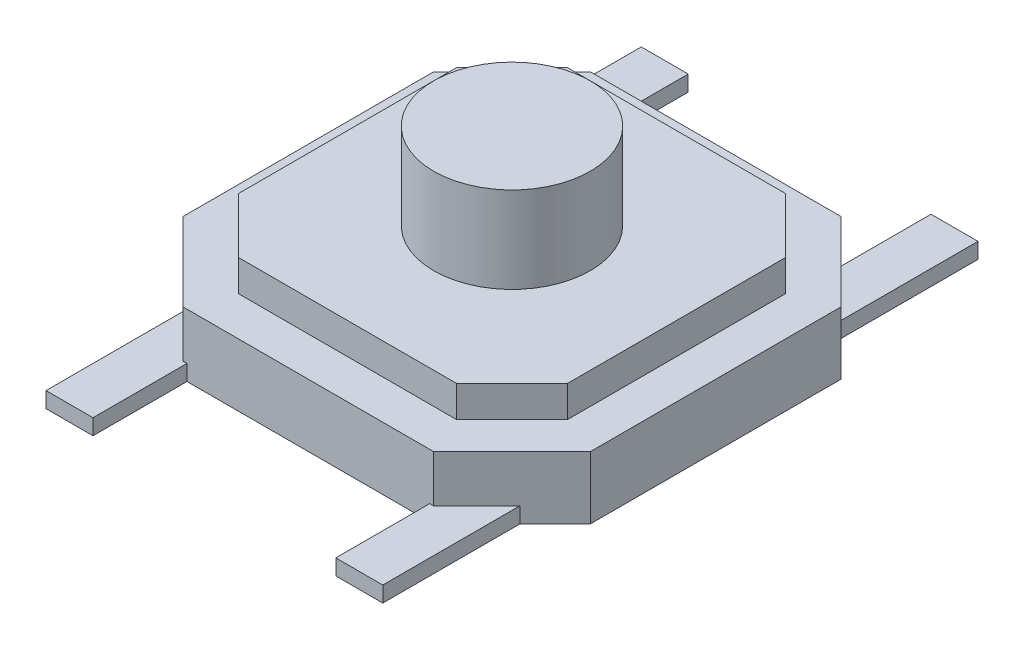
SolidWorks part; units mm, degrees
ref_plane "前视" through (0, 0, 0) normal (0, 0, 1) x (1, 0, 0)
ref_plane "上视" through (0, 0, 0) normal (0, 1, 0) x (1, 0, 0)
ref_plane "右视" through (0, 0, 0) normal (1, 0, 0) x (0, 0, -1)
sketch "草图1" plane through (0, 0, 0) normal (0, 1, 0) x (1, 0, 0)
  line L0 (0, 96.9306) -> (0, -101.3275) construction
  line L1 (-119.7143, 0) -> (134.9034, 0) construction
  line L3 (-2.6, 2.6) -> (2.6, 2.6)
  line L4 (-2.6, 2.6) -> (-2.6, -2.6)
  line L5 (-2.6, -2.6) -> (2.6, -2.6)
  line L6 (2.6, 2.6) -> (2.6, -2.6)
  dimension "D1" = 5.2
  dimension "D2" = 5.2
extrude "拉伸1" add sketch "草图1" along normal blind 0.8
chamfer "倒角1" distance 1 angle 45 4 edges at (2.6, 0.4, -2.6) (2.6, 0.4, 2.6) (-2.6, 0.4, 2.6) (-2.6, 0.4, -2.6)
sketch "草图3" plane through (0, 0.8, 0) normal (0, 1, 0) x (1, 0, 0)
  line L16 (-2.1, 1.3929) -> (-2.1, -1.3929)
  line L17 (-2.1, -1.3929) -> (-1.3929, -2.1)
  line L18 (-1.3929, -2.1) -> (1.3929, -2.1)
  line L19 (1.3929, -2.1) -> (2.1, -1.3929)
  line L20 (2.1, -1.3929) -> (2.1, 1.3929)
  line L21 (2.1, 1.3929) -> (1.3929, 2.1)
  line L22 (1.3929, 2.1) -> (-1.3929, 2.1)
  line L23 (-1.3929, 2.1) -> (-2.1, 1.3929)
  line L24 (-2.1, 1.3929) -> (-2.1, -1.3929)
  line L25 (-2.1, -1.3929) -> (-1.3929, -2.1)
  line L26 (-1.3929, -2.1) -> (1.3929, -2.1)
  line L27 (1.3929, -2.1) -> (2.1, -1.3929)
  line L28 (2.1, -1.3929) -> (2.1, 1.3929)
  line L29 (2.1, 1.3929) -> (1.3929, 2.1)
  line L30 (1.3929, 2.1) -> (-1.3929, 2.1)
  line L31 (-1.3929, 2.1) -> (-2.1, 1.3929)
  dimension "D1" = 0.5
extrude "凸台-拉伸1" add sketch "草图3" along normal offset from surface (0.4 mm away) 1.2 up to face at (0, 0, 0)
sketch "草图2" plane through (0, 1.2, 0) normal (0, 1, 0) x (-1, 0, 0)
  line L0 (-2.6, 0) -> (8.7109, 0) construction
  line L1 (-2.6, 1.6) -> (-2.6, -1.6) construction
  line L2 (0, -7.8518) -> (0, 10.0992) construction
  circle A0 centre (0, 0) radius 1
  dimension "D1" = 2
extrude "高度" add sketch "草图2" along normal offset from surface (1.1 mm away) 2.3 up to face at (0, 0, 0)
sketch "草图4" plane through (0, 0, 0) normal (0, -1, 0) x (1, 0, 0)
  line L0 (0, 5.6043) -> (0, -6.529) construction
  line L1 (-7.8223, 0) -> (5.922, 0) construction
  line L3 (-1.55, 1.1317) -> (-2.15, 1.1317)
  line L4 (-1.55, 1.1317) -> (-1.55, 3.8)
  line L5 (-1.55, 3.8) -> (-2.15, 3.8)
  line L6 (-2.15, 1.1317) -> (-2.15, 3.8)
  line L7 (-1.85, 4.1914) -> (-1.85, 0.5446) construction
  line L8 (1.85, 4.1914) -> (1.85, 0.5446) construction
  line L9 (2.15, 1.1317) -> (2.15, 3.8)
  line L10 (1.55, 3.8) -> (2.15, 3.8)
  line L11 (1.55, 1.1317) -> (1.55, 3.8)
  line L12 (1.55, 1.1317) -> (2.15, 1.1317)
  line L13 (1.85, -4.1914) -> (1.85, -0.5446) construction
  line L14 (-1.85, -4.1914) -> (-1.85, -0.5446) construction
  line L15 (1.55, -1.1317) -> (2.15, -1.1317)
  line L16 (1.55, -1.1317) -> (1.55, -3.8)
  line L17 (1.55, -3.8) -> (2.15, -3.8)
  line L18 (2.15, -1.1317) -> (2.15, -3.8)
  line L19 (-2.15, -1.1317) -> (-2.15, -3.8)
  line L20 (-1.55, -3.8) -> (-2.15, -3.8)
  line L21 (-1.55, -1.1317) -> (-1.55, -3.8)
  line L22 (-1.55, -1.1317) -> (-2.15, -1.1317)
  dimension "D1" = 0.6
  dimension "D2" = 7.6
  dimension "D3" = 3.7
extrude "凸台-拉伸2" add sketch "草图4" against normal blind 0.2
